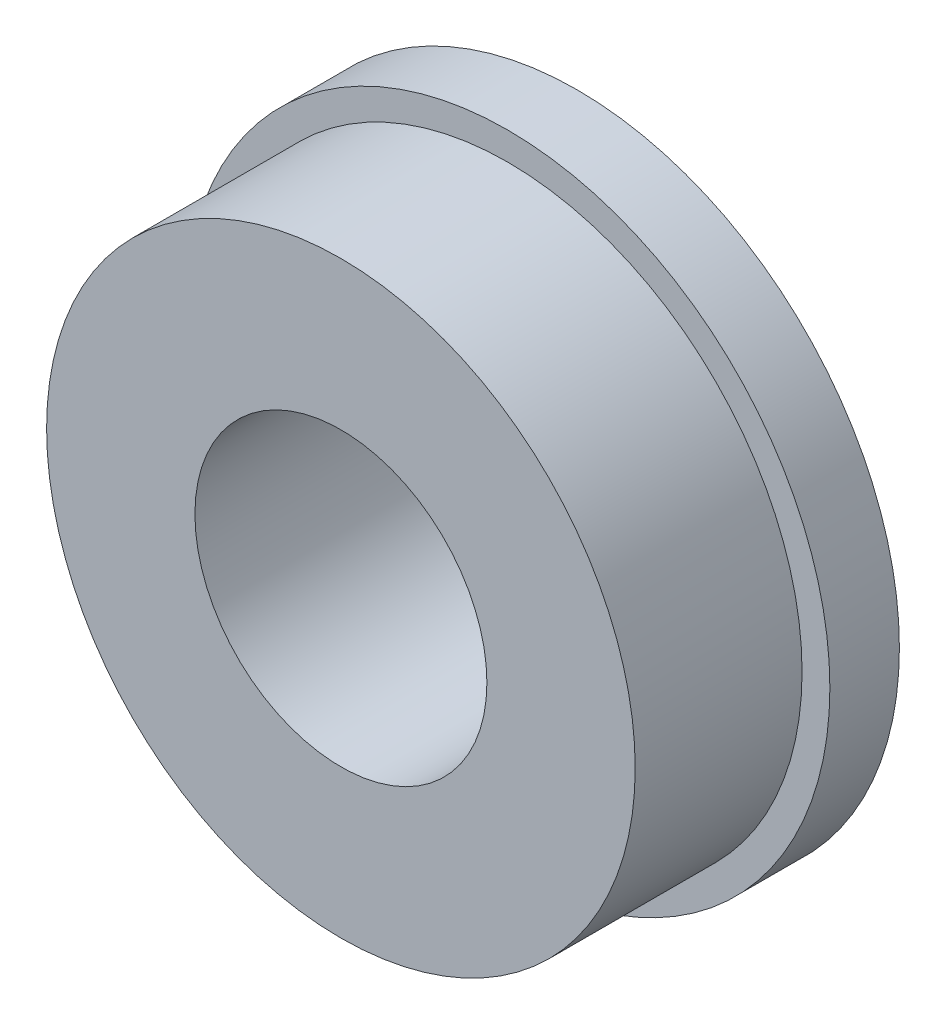
SolidWorks part; units mm, degrees
ref_plane "Alzado" through (0, 0, 0) normal (0, 0, 1) x (1, 0, 0)
ref_plane "Planta" through (0, 0, 0) normal (0, 1, 0) x (1, 0, 0)
ref_plane "Vista lateral" through (0, 0, 0) normal (1, 0, 0) x (0, 0, -1)
sketch "Croquis1" plane through (0, 0, 0) normal (0, 0, 1) x (1, 0, 0)
  circle A0 centre (0, 0) radius 6.95
  dimension "D1" = 13.9
extrude "Saliente-Extruir1" add sketch "Croquis1" along normal blind 1.5
sketch "Croquis2" plane through (0, 0, 1.5) normal (0, 0, 1) x (1, 0, 0)
  circle A0 centre (0, 0) radius 6.35
  dimension "D1" = 12.7
extrude "Saliente-Extruir2" add sketch "Croquis2" along normal blind 3.6
sketch "Croquis3" plane through (0, 0, 5.1) normal (0, 0, 1) x (1, 0, 0)
  circle A0 centre (0, 0) radius 3.15
  dimension "D1" = 6.3
extrude "Cortar-Extruir1" cut sketch "Croquis3" against normal through all
